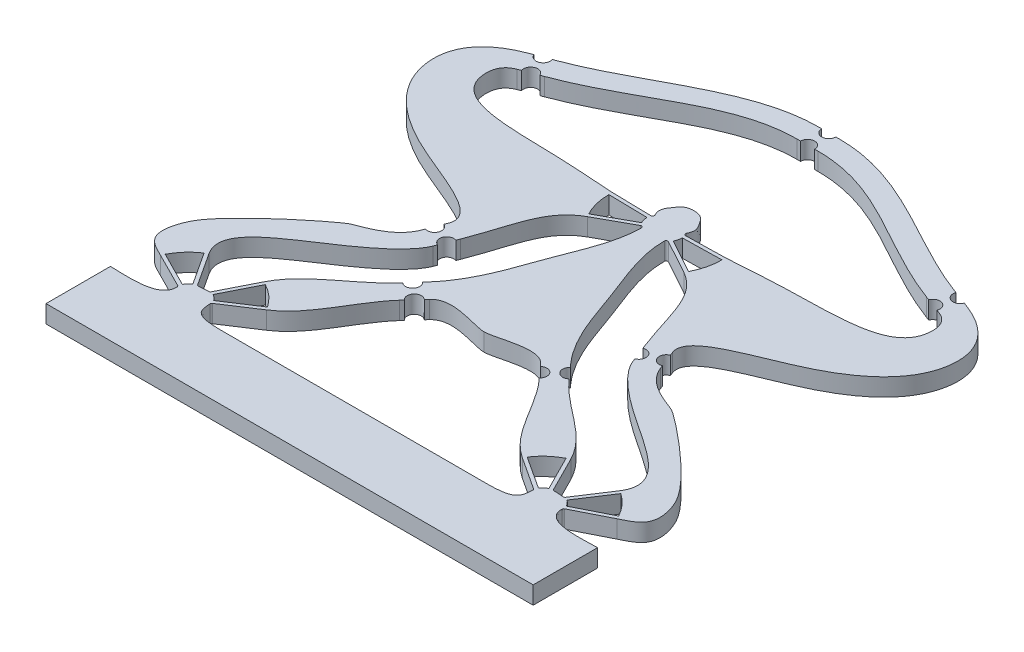
SolidWorks part; units mm, degrees
ref_plane "Front Plane" through (0, 0, 0) normal (0, 0, 1) x (1, 0, 0)
ref_plane "Top Plane" through (0, 0, 0) normal (0, 1, 0) x (1, 0, 0)
ref_plane "Right Plane" through (0, 0, 0) normal (1, 0, 0) x (0, 0, -1)
sketch "Basic" plane through (0, 0, 0) normal (0, 1, 0) x (1, 0, 0)
  line L0 (-100, 0) -> (-40, 67.082) construction
  line L1 (-40, 67.082) -> (0, 169.5515) construction
  line L2 (0, 169.5515) -> (-60, 102.4695) construction
  line L3 (-60, 102.4695) -> (-100, 0) construction
  line L4 (-40, 67.082) -> (40, 67.082) construction
  line L5 (-60, 102.4695) -> (-115.9233, 212.8627) construction
  line L6 (-115.9233, 212.8627) -> (0, 169.5515) construction
  line L7 (-115.9233, 212.8627) -> (0, 256.1738) construction
  line L8 (0, 256.1738) -> (0, 169.5515) construction
  line L9 (115.9233, 212.8627) -> (0, 256.1738) construction
  line L10 (115.9233, 212.8627) -> (0, 169.5515) construction
  line L11 (60, 102.4695) -> (115.9233, 212.8627) construction
  line L12 (60, 102.4695) -> (100, 0) construction
  line L13 (0, 169.5515) -> (60, 102.4695) construction
  line L14 (40, 67.082) -> (0, 169.5515) construction
  line L15 (100, 0) -> (40, 67.082) construction
  point P0 (-100, 0)
  point P1 (-40, 67.082)
  point P2 (0, 169.5515)
  point P14 (0, 67.082)
  dimension "l1/2" = 100
  dimension "l2" = 90
  dimension "l3/2" = 40
  dimension "couplerLength" = 110
  dimension "couplerAngle" = 68.676
  dimension "couplerAngle2" = 68.676
  dimension "D1" = 68.676
  dimension "OAngle" = 69.513
  dimension "D3" = 69.513
sketch "Sketch4" plane through (0, 0, 0) normal (0, 1, 0) x (1, 0, 0)
  line L0 (-50.1021, 76.1176) -> (-24.4518, 53.1753) construction
  line L1 (0, 256.1738) -> (0, 169.5515) construction
  line L2 (-31.4082, 76.6879) -> (-47.0503, 59.1995) construction
  line L3 (-17.3455, -73.9284) -> (-182.6545, 73.9284) construction
  line L4 (-47.1452, 68.1063) -> (-48.4785, 66.6156)
  line L5 (-38.1882, 60.0949) -> (-39.5215, 58.6042)
  line L6 (-32.8548, 66.0578) -> (-31.5215, 67.5485)
  line L7 (-41.8118, 74.0692) -> (-40.4785, 75.5599)
  line L8 (-8.808, 205.2724) -> (8.808, 133.8307) construction
  line L9 (-95.049, 8.6884) -> (-85.1223, 28.3311)
  line L10 (-8.989, 165.1701) -> (-28.2658, 154.55)
  line L11 (-96.8794, 9.5006) -> (-86.9214, 29.2053)
  line L12 (-100, 0) -> (-129.1748, -32.6184) construction
  line L13 (-86.9214, 29.2053) -> (-96.8794, 9.5006)
  line L14 (-7.9358, 163.4669) -> (-27.2733, 152.8134)
  line L15 (0, 169.5515) -> (-60, 102.4695) construction
  line L16 (-115.9233, 212.8627) -> (0, 169.5515) construction
  line L17 (0, 169.5515) -> (42.4895, 180.0285) construction
  line L18 (-100, 0) -> (-40, 67.082) construction
  line L19 (-115.9233, 212.8627) -> (0, 256.1738) construction
  line L20 (-55.8653, 96.5615) -> (-56.5926, 94.6984)
  line L21 (-64.1347, 108.3775) -> (-63.4074, 110.2406)
  line L22 (-72.6255, 107.398) -> (-40.483, 94.8509) construction
  line L23 (-52.9562, 104.0139) -> (-52.2289, 105.8769)
  line L24 (-55.61, 113.7156) -> (-64.28, 91.5052) construction
  line L25 (-67.0438, 100.9252) -> (-67.7711, 99.0621)
  line L26 (-121.6167, 228.1012) -> (-109.5404, 195.7788) construction
  line L27 (-121.7702, 217.0832) -> (-123.6438, 216.3832)
  line L28 (-110.0763, 208.6421) -> (-108.2028, 209.3421)
  line L29 (-103.9501, 217.3361) -> (-126.2848, 208.9914) construction
  line L30 (-117.5704, 205.8422) -> (-119.4439, 205.1422)
  line L31 (-114.2762, 219.8831) -> (-112.4027, 220.5831)
  line L32 (-60, 102.4695) -> (-100, 0) construction
  line L33 (-27.2733, 152.8134) -> (-7.9358, 163.4669)
  line L34 (-72.4287, 16.2427) -> (-90.9049, 4.1569)
  line L35 (-90.9049, 4.1569) -> (-72.4287, 16.2427)
  line L36 (-31.9283, 171.6919) -> (-9.8548, 171.2494)
  line L37 (-9.8548, 171.2494) -> (-31.9283, 171.6919)
  line L38 (12.8937, 256.1738) -> (-10.9489, 256.1738) construction
  line L39 (0, 265.543) -> (0, 231.0383) construction
  line L40 (4, 250.1738) -> (6, 250.1738) construction
  line L41 (4, 262.1738) -> (6, 262.1738) construction
  line L42 (-4, 250.1738) -> (-6, 250.1738)
  line L43 (-4, 262.1738) -> (-6, 262.1738)
  line L44 (-9.9955, 169.2518) -> (-31.9997, 169.693)
  line L45 (-91.9155, 5.8857) -> (-73.4974, 17.9335)
  line L46 (-115.4672, -17.2929) -> (-84.5328, 17.2929) construction
  line L47 (-108.6884, 4.951) -> (-128.3311, 14.8777)
  line L48 (-109.5006, 3.1206) -> (-129.2053, 13.0786)
  line L49 (-100, 0) -> (-67.2957, -29.2516) construction
  line L50 (-129.2053, 13.0786) -> (-109.5006, 3.1206)
  line L51 (-116.2427, 27.5713) -> (-104.1569, 9.0951)
  line L52 (-104.1569, 9.0951) -> (-116.2427, 27.5713)
  line L53 (-105.8857, 8.0845) -> (-117.9335, 26.5026)
  line L54 (0, 185.8984) -> (-14.1025, 185.8984) construction
  line L55 (0, -6.5819) -> (-75.2651, -6.5819)
  line L56 (-137.8734, -6.5819) -> (-137.8734, -43.045)
  line L57 (-40, 67.082) -> (40, 67.082) construction
  line L58 (-137.8734, -43.045) -> (0, -43.045)
  line L59 (-103.2644, 8.644) -> (-97.7163, 8.9532)
  line L60 (0, -6.5819) -> (0, -43.045)
  line L61 (0, 185.8984) -> (0, 67.082)
  line L62 (0, 258.1738) -> (0, 254.1738)
  arc A0 (-47.1452, 68.1063) -> (-41.8118, 74.0692) centre (-44.4721, 71.082) ccw
  arc A1 (-38.1882, 60.0949) -> (-32.8548, 66.0578) centre (-35.5279, 63.082) cw
  arc A2 (-6.4533, 162.591) -> (-7.9358, 163.4669) centre (-7.4533, 162.591) ccw
  arc A3 (-97.7163, 8.9532) -> (-96.8794, 9.5006) centre (-97.7719, 9.9517) ccw
  arc A4 (-73.4974, 17.9335) -> (-85.1223, 28.3311) centre (-100, 0) ccw
  arc A5 (-31.9997, 169.693) -> (-28.2658, 154.55) centre (0, 169.5515) ccw
  arc A6 (-55.8653, 96.5615) -> (-52.9562, 104.0139) centre (-54.4108, 100.2877) cw
  arc A7 (-67.0438, 100.9252) -> (-64.1347, 108.3775) centre (-65.5892, 104.6513) ccw
  arc A8 (-121.7702, 217.0832) -> (-114.2762, 219.8831) centre (-118.0232, 218.4832) ccw
  arc A9 (-117.5704, 205.8422) -> (-110.0763, 208.6421) centre (-113.8234, 207.2421) cw
  arc A10 (-95.049, 8.6884) -> (-91.9155, 5.8857) centre (-100, 0) cw
  arc A11 (-91.356, 3.2644) -> (-90.9049, 4.1569) centre (-90.3575, 3.32) cw
  arc A12 (-4, 250.1738) -> (0, 254.1738) centre (0, 250.1738) cw
  arc A13 (-4, 262.1738) -> (0, 258.1738) centre (0, 262.1738) ccw
  arc A14 (-108.9532, 2.2837) -> (-109.5006, 3.1206) centre (-109.9517, 2.2281) ccw
  arc A15 (-117.9335, 26.5026) -> (-128.3311, 14.8777) centre (-100, 0) ccw
  arc A16 (-8.989, 165.1701) -> (-9.9955, 169.2518) centre (0, 169.5515) cw
  arc A17 (-8.9494, 172.7141) -> (-9.8548, 171.2494) centre (-9.8348, 172.2492) cw
  arc A18 (-108.6884, 4.951) -> (-105.8857, 8.0845) centre (-100, 0) cw
  arc A19 (-103.2644, 8.644) -> (-104.1569, 9.0951) centre (-103.32, 9.6425) cw
  spline S0 degree 3 poles (-108.2028, 209.3421) (-69.2396, 223.8995) (-42.6858, 250.1738) (-6, 250.1738) knots 0 0 0 0 1 1 1 1
  spline S1 degree 3 poles (-112.4027, 220.5831) (-76.7304, 233.911) (-44.0894, 262.1738) (-6, 262.1738) knots 0 0 0 0 1 1 1 1
  spline S2 degree 3 poles (-27.2733, 152.8134) (-42.7933, 144.263) (-43.9497, 127.0863) (-52.2289, 105.8769) knots 0 0 0 0 1 1 1 1
  spline S3 degree 3 poles (-119.4439, 205.1422) (-125.6717, 202.8154) (-131.1957, 172.2284) (-78.3016, 175.6405) (-35.272, 171.759) (-31.9283, 171.6919) knots 0 0 0 0 0.124419 0.71001 1 1 1 1
  spline S4 degree 3 poles (-123.6438, 216.3832) (-146.4506, 207.8622) (-155.1315, 174.1257) (-116.9868, 138.2272) (-58.4296, 122.9925) (-63.4074, 110.2406) knots 0 0 0 0 0.283699 0.638824 1 1 1 1
  spline S5 degree 3 poles (-72.4287, 16.2427) (-57.3931, 26.0778) (-51.4419, 45.2768) (-39.5215, 58.6042) knots 0 0 0 0 1 1 1 1
  spline S6 degree 3 poles (-86.9214, 29.2053) (-78.8178, 45.2406) (-60.3989, 53.2882) (-48.4785, 66.6156) knots 0 0 0 0 1 1 1 1
  spline S7 degree 3 poles (-129.2053, 13.0786) (-136.2083, 16.6177) (-144.8568, 19.5403) (-133.6814, 48.6938) (-96.1986, 79.2673) (-87.8504, 83.6785) (-71.8587, 88.5907) (-67.7711, 99.0621) knots 0 0 0 0 0.398717 0.477576 0.754035 0.809733 1 1 1 1
  spline S8 degree 3 poles (-116.2427, 27.5713) (-124.0579, 39.5189) (-106.0165, 54.5931) (-73.9471, 74.4019) (-59.0286, 88.458) (-56.5926, 94.6984) knots 0 0 0 0 0.503887 0.777241 1 1 1 1
  spline S9 degree 3 poles (-6.4533, 162.591) (-6.4533, 148.7712) (-20.0266, 119.2111) (-28.0596, 89.4446) (-40.4785, 75.5599) knots 0 0 0 0 0.440914 1 1 1 1
  spline S10 degree 3 poles (-31.5215, 67.5485) (-24.5302, 75.365) (-6.5586, 67.082) (0, 67.082) knots 0 0 0 0 1 1 1 1
  spline S11 degree 3 poles (-8.9494, 172.7141) (-10.9706, 176.5634) (-7.6165, 181.239) (-4.8136, 185.8984) (0, 185.8984) knots 0 0 0 0 0.470593 1 1 1 1
  spline S12 degree 3 poles (-91.356, 3.2644) (-91.1374, -0.6575) (-90.2577, -4.9067) (-83.0766, -6.5819) (-75.2651, -6.5819) knots 0 0 0 0 0.47648 1 1 1 1
  spline S13 degree 3 poles (-108.9532, 2.2837) (-108.3186, -9.1032) (-129.4455, -6.5819) (-137.8734, -6.5819) knots 0 0 0 0 1 1 1 1
  dimension "D1" = 4
  dimension "D3" = 8
  dimension "D6" = 10
  dimension "D11" = 10.198
  dimension "D16" = 4
  dimension "D21" = 4
  dimension "D26" = 10
  dimension "D31" = 4
  dimension "D7" = 32
  dimension "D10" = 1
  dimension "D13" = 1
  dimension "D8" = 2
  dimension "D15" = 32
  dimension "D29" = 1
  dimension "D36" = 32
  dimension "D37" = 10
  dimension "D2" = 6
  dimension "D4" = 2
  dimension "D5" = 2
  dimension "D9" = 2
  dimension "D12" = 15
  dimension "D14" = 10.198
  dimension "D17" = 6
  dimension "D18" = 8
  dimension "D19" = 2
  dimension "D20" = 15
  dimension "D22" = 6
  dimension "D23" = 8
  dimension "D24" = 2
  dimension "D25" = 2
  dimension "D27" = 15
  dimension "D28" = 2
  dimension "D30" = 10.198
  dimension "D32" = 6
  dimension "D33" = 8
  dimension "D34" = 2
  dimension "D35" = 2
sketch "Sketch5" plane through (0, 0, 0) normal (0, 1, 0) x (1, 0, 0)
  line L0 (-14.0529, 35.7209) -> (3.5631, -35.7209) construction
  line L1 (-14.234, -4.3814) -> (-33.5107, -15.0015)
  line L2 (-13.1807, -6.0846) -> (-32.5182, -16.7382)
  line L3 (-5.2449, 0) -> (37.2446, 10.477) construction
  line L4 (-32.5182, -16.7382) -> (-13.1807, -6.0846)
  line L5 (-32.8384, 16.2049) -> (-13.6886, 5.3576)
  line L6 (-33.7969, 14.4493) -> (-14.5868, 3.5678)
  line L7 (-37.1732, 2.1404) -> (-15.0997, 1.6979)
  line L8 (-15.0997, 1.6979) -> (-37.1732, 2.1404)
  line L9 (-15.2404, -0.2997) -> (-37.2446, 0.1414)
  line L10 (-23.8067, -26.0665) -> (-11.8573, -7.5017)
  line L11 (-22.1418, -27.1752) -> (-10.23, -8.6688)
  arc A0 (-11.8573, -7.5017) -> (-13.1807, -6.0846) centre (-12.6982, -6.9605) ccw
  arc A1 (-14.234, -4.3814) -> (-13.1807, -6.0846) centre (-5.2449, 0) ccw
  arc A2 (-11.8573, -7.5017) -> (-10.23, -8.6688) centre (-5.2449, 0) ccw
  arc A3 (-33.5107, -15.0015) -> (-32.5182, -16.7382) centre (-5.2449, 0) ccw
  arc A4 (-23.8067, -26.0665) -> (-22.1418, -27.1752) centre (-5.2449, 0) ccw
  arc A5 (-33.7969, 14.4493) -> (-32.8384, 16.2049) centre (-5.2449, 0) cw
  arc A6 (-37.2446, 0.1414) -> (-37.1732, 2.1404) centre (-5.2449, 0) cw
  arc A7 (-14.5868, 3.5678) -> (-13.6886, 5.3576) centre (-5.2449, 0) cw
  arc A8 (-14.234, -4.3814) -> (-15.2404, -0.2997) centre (-5.2449, 0) cw
  arc A9 (-14.5868, 3.5678) -> (-15.0997, 1.6979) centre (-15.0797, 2.6977) cw
  point P8 (-16.1859, -17.922)
  dimension "D1" = 64
  dimension "D4" = 1
  dimension "D7" = 10
  dimension "D2" = 2
  dimension "D3" = 2
  dimension "D5" = 10.198
  dimension "D6" = 15
extrude "Boss-Extrude1" add sketch "Sketch4" along normal blind 10
mirror "Mirror1" about plane through (0, 10, 0) normal (1, 0, 0) of bodies 101
equation "\"couplerAngle\"= \"couplerAngle@Basic\""
equation "\"couplerAngle2@Basic\"=\"couplerAngle\""
equation "\"D1@Basic\"=\"couplerAngle\""
equation "\"OAngle\"= \"OAngle@Basic\""
equation "\"D3@Basic\"=\"OAngle\""
equation "\"beta\"= 0.25"
equation "\"t\"= 2mm"
equation "\"D\"= \"t\" / \"beta\""
